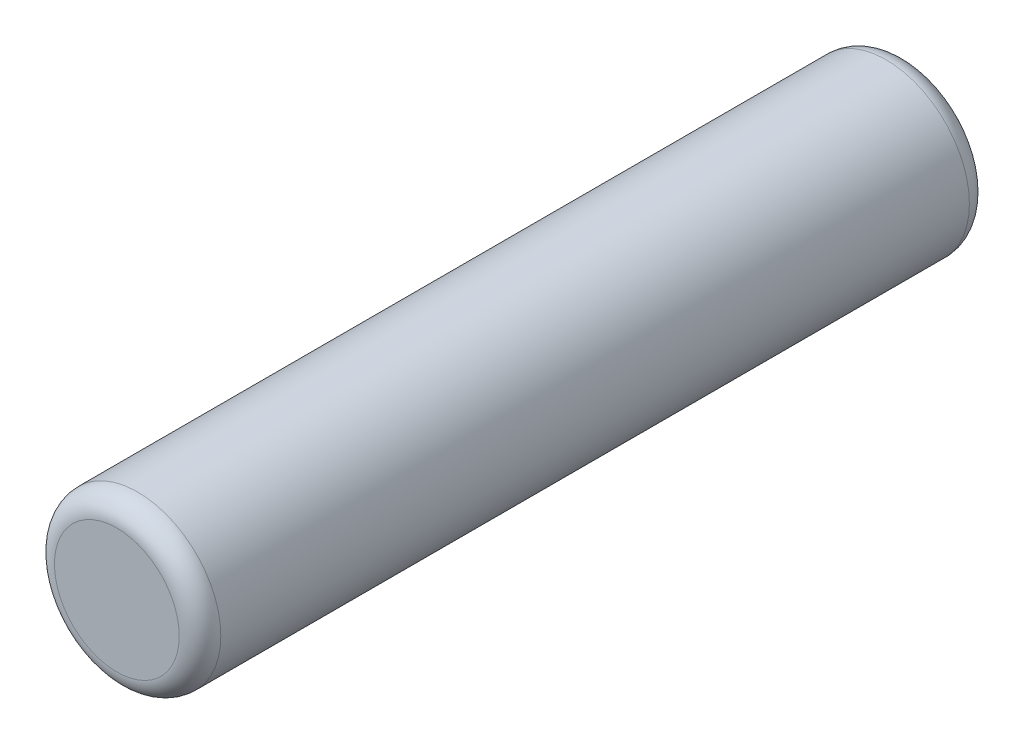
SolidWorks part; units mm, degrees
ref_plane "Front Plane" through (0, 0, 0) normal (0, 0, 1) x (1, 0, 0)
ref_plane "Top Plane" through (0, 0, 0) normal (0, 1, 0) x (1, 0, 0)
ref_plane "Right Plane" through (0, 0, 0) normal (1, 0, 0) x (0, 0, -1)
sketch "Sketch1" plane through (0, 0, 0) normal (0, 0, 1) x (1, 0, 0)
  circle A0 centre (0, 0) radius 2
  dimension "D1" = 4
extrude "Boss-Extrude1" add sketch "Sketch1" against normal blind 19
fillet "Fillet1" radius 0.5 1 edges at (2, 0, -19)
fillet "Fillet2" radius 0.5 1 edges at (2, 0, 0)
